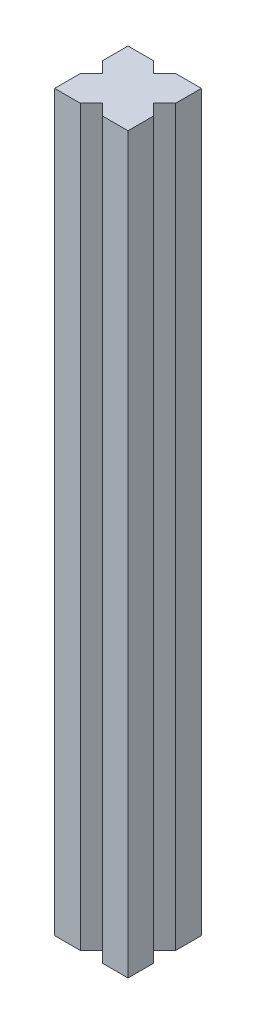
SolidWorks part; units mm, degrees
ref_plane "Front" through (0, 0, 0) normal (0, 0, 1) x (1, 0, 0)
ref_plane "Top" through (0, 0, 0) normal (0, 1, 0) x (1, 0, 0)
ref_plane "Right" through (0, 0, 0) normal (1, 0, 0) x (0, 0, -1)
sketch "Skizze1" plane through (0, 0, 0) normal (0, 1, 0) x (1, 0, 0)
  line L1 (0, 0) -> (20, 0)
  line L2 (0, 0) -> (0, 20)
  line L3 (0, 20) -> (20, 20)
  line L4 (20, 0) -> (20, 20)
  dimension "D1" = 20
extrude "Aufsatz-Linear austragen1" add sketch "Skizze1" along normal blind 200
sketch "Skizze2" plane through (0, 200, 0) normal (0, 1, 0) x (1, 0, 0)
  line L0 (10, 20) -> (10, 0) construction
  line L1 (0, 10) -> (20, 10) construction
  line L2 (7, 20) -> (10, 17)
  line L3 (13, 20) -> (10, 17)
  line L4 (10, 10) -> (20, 20) construction
  line L5 (7, 20) -> (13, 20)
  line L6 (20, 13) -> (17, 10)
  line L7 (20, 7) -> (17, 10)
  line L8 (20, 7) -> (20, 13)
  line L9 (0, 7) -> (0, 13)
  line L10 (0, 7) -> (3, 10)
  line L11 (0, 13) -> (3, 10)
  line L12 (7, 0) -> (13, 0)
  line L13 (13, 0) -> (10, 3)
  line L14 (7, 0) -> (10, 3)
  line L15 (20, 20) -> (0, 20) construction
  line L16 (20, 0) -> (20, 20) construction
  line L17 (0, 0) -> (20, 0) construction
  dimension "D1" = 3
  dimension "D2" = 3
extrude "Schnitt-Linear austragen1" cut sketch "Skizze2" against normal through all
ref_plane "Ebene1" through (10, 0, 0) normal (-1, 0, 0) x (0, 0, 1)
